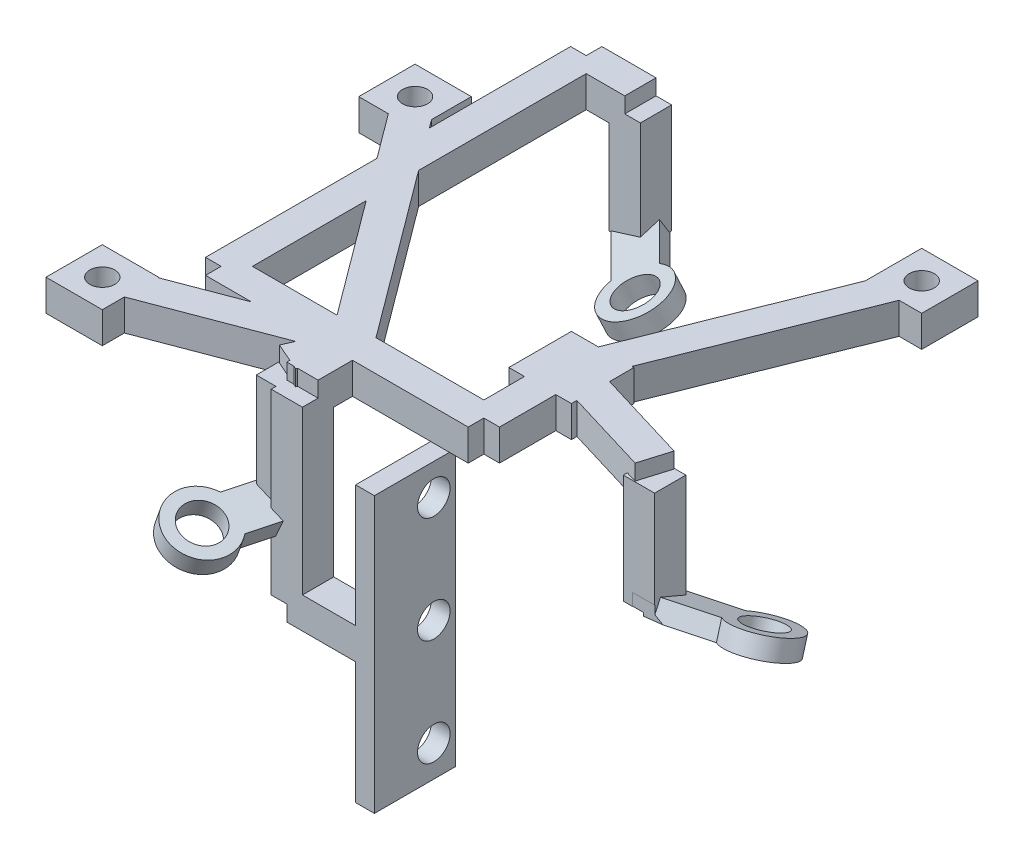
SolidWorks part; units mm, degrees
other "Cable Fairlead Support Frame"
other "Cable Fairlead Support Frame Left"
ref_plane "Front Plane" through (0, 0, 0) normal (0, 0, 1) x (1, 0, 0)
ref_plane "Top Plane" through (0, 0, 0) normal (0, 1, 0) x (1, 0, 0)
ref_plane "Right Plane" through (0, 0, 0) normal (1, 0, 0) x (0, 0, -1)
sketch3d "Cable Fairlead Support Frame Feature profile datum points"
  point P0 (-55.2917, -60, -5)
  point P1 (-45.2917, -60, -5)
  point P2 (-55.2917, -50, -5)
ref_plane "Cable Fairlead Support Frame Feature profile plane" through (0, 0, -5) normal (0, 0, 1) x (1, 0, 0)
sketch "Cable Fairlead Support Frame Feature profile" plane through (0, 0, -5) normal (0, 0, 1) x (1, 0, 0)
  line L0 (-55.2917, -60) -> (-45.2917, -60)
  line L1 (-45.2917, -60) -> (-45.2917, -55)
  line L2 (-45.2917, -55) -> (-55.2917, -55)
  line L3 (-55.2917, -55) -> (-55.2917, -60)
extrude "Cable Fairlead Support Frame Feature" add sketch "Cable Fairlead Support Frame Feature profile" along normal blind 10 separate body
sketch3d "Frame Upper Trunk Sketch datum points"
  point P0 (-50.2917, -57.5, 0)
  point P1 (-40.2917, -57.5, 0)
  point P2 (-50.2917, -47.5, 0)
ref_plane "Frame Upper Trunk Sketch plane" through (0, 0, 0) normal (0, 0, 1) x (1, 0, 0)
sketch "Frame Upper Trunk Sketch" plane through (0, 0, 0) normal (0, 0, 1) x (1, 0, 0)
  line L0 (-52.7917, -60) -> (-47.7917, -60)
  line L1 (-47.7917, -60) -> (-47.7917, -55)
  line L2 (-47.7917, -55) -> (-52.7917, -55)
  line L3 (-52.7917, -55) -> (-52.7917, -60)
extrude "Frame Upper Trunk Feature" add sketch "Frame Upper Trunk Sketch" along normal blind 14
sketch3d "Frame Left Trunk Sketch datum points"
  point P0 (-50.2917, -57.5, 14)
  point P1 (-50.2917, -57.5, 24)
  point P2 (-50.2917, -47.5, 14)
ref_plane "Frame Left Trunk Sketch plane" through (-50.2917, 0, 0) normal (-1, 0, 0) x (0, 0, 1)
sketch "Frame Left Trunk Sketch" plane through (-50.2917, 0, 0) normal (-1, 0, 0) x (0, 0, 1)
  line L0 (11.5, -60) -> (16.5, -60)
  line L1 (16.5, -60) -> (16.5, -55)
  line L2 (16.5, -55) -> (11.5, -55)
  line L3 (11.5, -55) -> (11.5, -60)
extrude "Frame Left Trunk Feature" add sketch "Frame Left Trunk Sketch" along normal blind 21
sketch3d "Fixed Frame Mounting Web 1 Sketch datum points"
  point P0 (-71.2917, -57.5, 14)
  point P1 (-79.3163, -57.5, 19.967)
  point P2 (-71.2917, -47.5, 14)
ref_plane "Fixed Frame Mounting Web 1 Sketch plane" through (-18.6801, 0, -25.1214) normal (-0.5967, 0, -0.8025) x (-0.8025, 0, 0.5967)
sketch "Fixed Frame Mounting Web 1 Sketch" plane through (-18.6801, 0, -25.1214) normal (-0.5967, 0, -0.8025) x (-0.8025, 0, 0.5967)
  line L0 (63.0627, -60) -> (68.0627, -60)
  line L1 (68.0627, -60) -> (68.0627, -55)
  line L2 (68.0627, -55) -> (63.0627, -55)
  line L3 (63.0627, -55) -> (63.0627, -60)
extrude "Fixed Frame Mounting Web 1 Feature" add sketch "Fixed Frame Mounting Web 1 Sketch" along normal blind 48.6004
sketch3d "Prismatic M4 Mounting Pad 1 profile datum points"
  point P0 (-104.7917, -60, -29.5)
  point P1 (-94.7917, -60, -29.5)
  point P2 (-104.7917, -50, -29.5)
ref_plane "Prismatic M4 Mounting Pad 1 profile plane" through (0, 0, -29.5) normal (0, 0, 1) x (1, 0, 0)
sketch "Prismatic M4 Mounting Pad 1 profile" plane through (0, 0, -29.5) normal (0, 0, 1) x (1, 0, 0)
  line L0 (-104.7917, -60) -> (-95.7917, -60)
  line L1 (-95.7917, -60) -> (-95.7917, -55)
  line L2 (-95.7917, -55) -> (-104.7917, -55)
  line L3 (-104.7917, -55) -> (-104.7917, -60)
extrude "Prismatic M4 Mounting Pad 1" add sketch "Prismatic M4 Mounting Pad 1 profile" along normal blind 9
sketch3d "Nominal M4 Mounting Thread 1 profile datum points"
  point P0 (-100.2917, -51, -25)
  point P1 (-90.2917, -51, -25)
  point P2 (-100.2917, -51, -15)
ref_plane "Nominal M4 Mounting Thread 1 profile plane" through (0, -51, 0) normal (0, -1, 0) x (-1, 0, 0)
sketch "Nominal M4 Mounting Thread 1 profile" plane through (0, -51, 0) normal (0, -1, 0) x (-1, 0, 0)
  circle A0 centre (100.2917, 25) radius 2
extrude "Nominal M4 Mounting Thread 1" cut sketch "Nominal M4 Mounting Thread 1 profile" along normal blind 9.1
sketch3d "Fixed Frame Mounting Web 2 Sketch datum points"
  point P0 (-71.2917, -57.5, 14)
  point P1 (-67.7451, -57.5, 23.35)
  point P2 (-71.2917, -47.5, 14)
ref_plane "Fixed Frame Mounting Web 2 Sketch plane" through (-66.967, 0, 25.4013) normal (-0.935, 0, 0.3547) x (0.3547, 0, 0.935)
sketch "Fixed Frame Mounting Web 2 Sketch" plane through (-66.967, 0, 25.4013) normal (-0.935, 0, 0.3547) x (0.3547, 0, 0.935)
  line L0 (-14.6939, -60) -> (-9.6939, -60)
  line L1 (-9.6939, -60) -> (-9.6939, -55)
  line L2 (-9.6939, -55) -> (-14.6939, -55)
  line L3 (-14.6939, -55) -> (-14.6939, -60)
extrude "Fixed Frame Mounting Web 2 Feature" add sketch "Fixed Frame Mounting Web 2 Sketch" along normal blind 31.0161
sketch3d "Prismatic M4 Mounting Pad 2 profile datum points"
  point P0 (-104.7917, -60, 20.5)
  point P1 (-94.7917, -60, 20.5)
  point P2 (-104.7917, -50, 20.5)
ref_plane "Prismatic M4 Mounting Pad 2 profile plane" through (0, 0, 20.5) normal (0, 0, 1) x (1, 0, 0)
sketch "Prismatic M4 Mounting Pad 2 profile" plane through (0, 0, 20.5) normal (0, 0, 1) x (1, 0, 0)
  line L0 (-104.7917, -60) -> (-95.7917, -60)
  line L1 (-95.7917, -60) -> (-95.7917, -55)
  line L2 (-95.7917, -55) -> (-104.7917, -55)
  line L3 (-104.7917, -55) -> (-104.7917, -60)
extrude "Prismatic M4 Mounting Pad 2" add sketch "Prismatic M4 Mounting Pad 2 profile" along normal blind 9
sketch3d "Nominal M4 Mounting Thread 2 profile datum points"
  point P0 (-100.2917, -51, 25)
  point P1 (-90.2917, -51, 25)
  point P2 (-100.2917, -51, 35)
ref_plane "Nominal M4 Mounting Thread 2 profile plane" through (0, -51, 0) normal (0, -1, 0) x (-1, 0, 0)
sketch "Nominal M4 Mounting Thread 2 profile" plane through (0, -51, 0) normal (0, -1, 0) x (-1, 0, 0)
  circle A0 centre (100.2917, -25) radius 2
extrude "Nominal M4 Mounting Thread 2" cut sketch "Nominal M4 Mounting Thread 2 profile" along normal blind 9.1
sketch3d "Fixed Frame Mounting Web 3 Sketch datum points"
  point P0 (-50.2917, -57.5, 0)
  point P1 (-59.5764, -57.5, -3.7139)
  point P2 (-50.2917, -47.5, 0)
ref_plane "Fixed Frame Mounting Web 3 Sketch plane" through (-6.9368, 0, 17.3419) normal (0.3714, 0, -0.9285) x (-0.9285, 0, -0.3714)
sketch "Fixed Frame Mounting Web 3 Sketch" plane through (-6.9368, 0, 17.3419) normal (0.3714, 0, -0.9285) x (-0.9285, 0, -0.3714)
  line L0 (44.1946, -60) -> (49.1946, -60)
  line L1 (49.1946, -60) -> (49.1946, -55)
  line L2 (49.1946, -55) -> (44.1946, -55)
  line L3 (44.1946, -55) -> (44.1946, -60)
extrude "Fixed Frame Mounting Web 3 Feature" add sketch "Fixed Frame Mounting Web 3 Sketch" along normal blind 43.0813
sketch3d "Prismatic M4 Mounting Pad 3 profile datum points"
  point P0 (-38.7917, -60, -44.5)
  point P1 (-28.7917, -60, -44.5)
  point P2 (-38.7917, -50, -44.5)
ref_plane "Prismatic M4 Mounting Pad 3 profile plane" through (0, 0, -44.5) normal (0, 0, 1) x (1, 0, 0)
sketch "Prismatic M4 Mounting Pad 3 profile" plane through (0, 0, -44.5) normal (0, 0, 1) x (1, 0, 0)
  line L0 (-38.7917, -60) -> (-29.7917, -60)
  line L1 (-29.7917, -60) -> (-29.7917, -55)
  line L2 (-29.7917, -55) -> (-38.7917, -55)
  line L3 (-38.7917, -55) -> (-38.7917, -60)
extrude "Prismatic M4 Mounting Pad 3" add sketch "Prismatic M4 Mounting Pad 3 profile" along normal blind 9
sketch3d "Nominal M4 Mounting Thread 3 profile datum points"
  point P0 (-34.2917, -51, -40)
  point P1 (-24.2917, -51, -40)
  point P2 (-34.2917, -51, -30)
ref_plane "Nominal M4 Mounting Thread 3 profile plane" through (0, -51, 0) normal (0, -1, 0) x (-1, 0, 0)
sketch "Nominal M4 Mounting Thread 3 profile" plane through (0, -51, 0) normal (0, -1, 0) x (-1, 0, 0)
  circle A0 centre (34.2917, 40) radius 2
extrude "Nominal M4 Mounting Thread 3" cut sketch "Nominal M4 Mounting Thread 3 profile" along normal blind 9.1
sketch3d "Outlet Side Rise Sketch datum points"
  point P0 (-71.2917, -57.5, 14)
  point P1 (-61.2917, -57.5, 14)
  point P2 (-71.2917, -47.5, 14)
ref_plane "Outlet Side Rise Sketch plane" through (0, 0, 14) normal (0, 0, 1) x (1, 0, 0)
sketch "Outlet Side Rise Sketch" plane through (0, 0, 14) normal (0, 0, 1) x (1, 0, 0)
  line L0 (-73.7917, -60) -> (-68.7917, -60)
  line L1 (-68.7917, -60) -> (-68.7917, -55)
  line L2 (-68.7917, -55) -> (-73.7917, -55)
  line L3 (-73.7917, -55) -> (-73.7917, -60)
extrude "Outlet Side Rise Feature" add sketch "Outlet Side Rise Sketch" along normal blind 8
sketch3d "Outlet Lateral Return Sketch datum points"
  point P0 (-71.2917, -57.5, 22)
  point P1 (-61.2917, -57.5, 22)
  point P2 (-71.2917, -57.5, 12)
ref_plane "Outlet Lateral Return Sketch plane" through (0, -57.5, 0) normal (0, 1, 0) x (1, 0, 0)
sketch "Outlet Lateral Return Sketch" plane through (0, -57.5, 0) normal (0, 1, 0) x (1, 0, 0)
  line L0 (-73.7917, -24.5) -> (-68.7917, -24.5)
  line L1 (-68.7917, -24.5) -> (-68.7917, -19.5)
  line L2 (-68.7917, -19.5) -> (-73.7917, -19.5)
  line L3 (-73.7917, -19.5) -> (-73.7917, -24.5)
extrude "Outlet Lateral Return Feature" add sketch "Outlet Lateral Return Sketch" along normal blind 28.5
sketch3d "Outlet Rail Bridge Sketch datum points"
  point P0 (-71.2917, -29, 22)
  point P1 (-71.2917, -29, 12)
  point P2 (-71.2917, -19, 22)
ref_plane "Outlet Rail Bridge Sketch plane" through (-71.2917, 0, 0) normal (1, 0, 0) x (0, 0, -1)
sketch "Outlet Rail Bridge Sketch" plane through (-71.2917, 0, 0) normal (1, 0, 0) x (0, 0, -1)
  line L0 (-24.5, -31.5) -> (-19.5, -31.5)
  line L1 (-19.5, -31.5) -> (-19.5, -26.5)
  line L2 (-19.5, -26.5) -> (-24.5, -26.5)
  line L3 (-24.5, -26.5) -> (-24.5, -31.5)
extrude "Outlet Rail Bridge Feature" add sketch "Outlet Rail Bridge Sketch" along normal blind 13
sketch3d "Integral Three Lane Cable Outlet Clamp Rail profile datum points"
  point P0 (-60.2917, -51, 11.5)
  point P1 (-50.2917, -51, 11.5)
  point P2 (-60.2917, -41, 11.5)
ref_plane "Integral Three Lane Cable Outlet Clamp Rail profile plane" through (0, 0, 11.5) normal (0, 0, 1) x (1, 0, 0)
sketch "Integral Three Lane Cable Outlet Clamp Rail profile" plane through (0, 0, 11.5) normal (0, 0, 1) x (1, 0, 0)
  line L0 (-60.2917, -51) -> (-57.2917, -51)
  line L1 (-57.2917, -51) -> (-57.2917, -7)
  line L2 (-57.2917, -7) -> (-60.2917, -7)
  line L3 (-60.2917, -7) -> (-60.2917, -51)
extrude "Integral Three Lane Cable Outlet Clamp Rail" add sketch "Integral Three Lane Cable Outlet Clamp Rail profile" along normal blind 13
sketch3d "Inlet Outrigger Web 1 Sketch datum points"
  point P0 (-50.2917, -57.5, 0)
  point P1 (-47.4006, -57.5, -9.573)
  point P2 (-50.2917, -47.5, 0)
ref_plane "Inlet Outrigger Web 1 Sketch plane" through (-46.0882, 0, -13.9187) normal (0.9573, 0, 0.2891) x (0.2891, 0, -0.9573)
sketch "Inlet Outrigger Web 1 Sketch" plane through (-46.0882, 0, -13.9187) normal (0.9573, 0, 0.2891) x (0.2891, 0, -0.9573)
  line L0 (-17.0396, -60) -> (-12.0396, -60)
  line L1 (-12.0396, -60) -> (-12.0396, -55)
  line L2 (-12.0396, -55) -> (-17.0396, -55)
  line L3 (-17.0396, -55) -> (-17.0396, -60)
extrude "Inlet Outrigger Web 1 Feature" add sketch "Inlet Outrigger Web 1 Sketch" along normal blind 19.8971
sketch3d "Inlet Vertical Support 1 Sketch datum points"
  point P0 (-31.2442, -57.5, 5.7524)
  point P1 (-21.2442, -57.5, 5.7524)
  point P2 (-31.2442, -57.5, -4.2476)
ref_plane "Inlet Vertical Support 1 Sketch plane" through (0, -57.5, 0) normal (0, 1, 0) x (1, 0, 0)
sketch "Inlet Vertical Support 1 Sketch" plane through (0, -57.5, 0) normal (0, 1, 0) x (1, 0, 0)
  line L0 (-33.7442, -8.2524) -> (-28.7442, -8.2524)
  line L1 (-28.7442, -8.2524) -> (-28.7442, -3.2524)
  line L2 (-28.7442, -3.2524) -> (-33.7442, -3.2524)
  line L3 (-33.7442, -3.2524) -> (-33.7442, -8.2524)
extrude "Inlet Vertical Support 1 Feature" add sketch "Inlet Vertical Support 1 Sketch" along normal blind 17.4581
sketch3d "Inlet Collar Retaining Web 1 Sketch datum points"
  point P0 (-31.2442, -40.0419, 5.7524)
  point P1 (-32.2823, -49.2023, 1.8781)
  point P2 (-33.6151, -36.031, -3.0959)
ref_plane "Inlet Collar Retaining Web 1 Sketch plane" through (-30.5893, 0, 8.1964) normal (0.9659, 0, -0.2588) x (-0.2588, 0, -0.9659)
sketch "Inlet Collar Retaining Web 1 Sketch" plane through (-30.5893, 0, 8.1964) normal (0.9659, 0, -0.2588) x (-0.2588, 0, -0.9659)
  line L0 (-0.8175, -39.8757) -> (0.3818, -42.6147)
  line L1 (0.3818, -42.6147) -> (5.878, -40.2081)
  line L2 (5.878, -40.2081) -> (4.6787, -37.4692)
  line L3 (4.6787, -37.4692) -> (-0.8175, -39.8757)
extrude "Inlet Collar Retaining Web 1 Feature" add sketch "Inlet Collar Retaining Web 1 Sketch" along normal blind 14
sketch3d "Integral Cable Guide Clamp 1 profile datum points"
  point P0 (-17.566, -38.6724, 2.7081)
  point P1 (-7.6201, -39.6285, 2.3037)
  point P2 (-17.566, -42.5677, 11.9182)
ref_plane "Integral Cable Guide Clamp 1 profile plane" through (-3.7579, -33.1604, -14.0246) normal (-0.1038, -0.916, -0.3874) x (-0.9946, 0.0956, 0.0404)
sketch "Integral Cable Guide Clamp 1 profile" plane through (-3.7579, -33.1604, -14.0246) normal (-0.1038, -0.916, -0.3874) x (-0.9946, 0.0956, 0.0404)
  circle A0 centre (13.8831, -17.5581) radius 5
extrude "Integral Cable Guide Clamp 1" add sketch "Integral Cable Guide Clamp 1 profile" along normal blind 2.99
sketch3d "Final Cable Inlet Clamp Through Bore 1 profile datum points"
  point P0 (-17.5546, -38.5717, 2.7507)
  point P1 (-7.6086, -39.5278, 2.3463)
  point P2 (-17.5546, -42.4669, 11.9609)
ref_plane "Final Cable Inlet Clamp Through Bore 1 profile plane" through (-3.7465, -33.0597, -13.982) normal (-0.1038, -0.916, -0.3874) x (-0.9946, 0.0956, 0.0404)
sketch "Final Cable Inlet Clamp Through Bore 1 profile" plane through (-3.7465, -33.0597, -13.982) normal (-0.1038, -0.916, -0.3874) x (-0.9946, 0.0956, 0.0404)
  circle A0 centre (13.8831, -17.5581) radius 3.1
extrude "Final Cable Inlet Clamp Through Bore 1" cut sketch "Final Cable Inlet Clamp Through Bore 1 profile" along normal blind 7.2
sketch3d "Inlet Outrigger Web 2 Sketch datum points"
  point P0 (-71.2917, -57.5, 14)
  point P1 (-62.124, -57.5, 17.9944)
  point P2 (-71.2917, -47.5, 14)
ref_plane "Inlet Outrigger Web 2 Sketch plane" through (-16.5011, 0, 37.8724) normal (-0.3994, 0, 0.9168) x (0.9168, 0, 0.3994)
sketch "Inlet Outrigger Web 2 Sketch" plane through (-16.5011, 0, 37.8724) normal (-0.3994, 0, 0.9168) x (0.9168, 0, 0.3994)
  line L0 (-62.2653, -60) -> (-57.2653, -60)
  line L1 (-57.2653, -60) -> (-57.2653, -55)
  line L2 (-57.2653, -55) -> (-62.2653, -55)
  line L3 (-62.2653, -55) -> (-62.2653, -60)
extrude "Inlet Outrigger Web 2 Feature" add sketch "Inlet Outrigger Web 2 Sketch" along normal blind 7.8874
sketch3d "Inlet Vertical Support 2 Sketch datum points"
  point P0 (-74.4422, -57.5, 21.2309)
  point P1 (-64.4422, -57.5, 21.2309)
  point P2 (-74.4422, -57.5, 11.2309)
ref_plane "Inlet Vertical Support 2 Sketch plane" through (0, -57.5, 0) normal (0, 1, 0) x (1, 0, 0)
sketch "Inlet Vertical Support 2 Sketch" plane through (0, -57.5, 0) normal (0, 1, 0) x (1, 0, 0)
  line L0 (-76.9422, -23.7309) -> (-71.9422, -23.7309)
  line L1 (-71.9422, -23.7309) -> (-71.9422, -18.7309)
  line L2 (-71.9422, -18.7309) -> (-76.9422, -18.7309)
  line L3 (-76.9422, -18.7309) -> (-76.9422, -23.7309)
extrude "Inlet Vertical Support 2 Feature" add sketch "Inlet Vertical Support 2 Sketch" along normal blind 17.4535
sketch3d "Inlet Collar Retaining Web 2 Sketch datum points"
  point P0 (-74.4422, -40.0465, 21.2309)
  point P1 (-70.568, -49.2069, 22.269)
  point P2 (-65.5939, -36.0356, 23.6018)
ref_plane "Inlet Collar Retaining Web 2 Sketch plane" through (-10.2944, 0, 38.4192) normal (-0.2588, 0, 0.9659) x (0.9659, 0, 0.2588)
sketch "Inlet Collar Retaining Web 2 Sketch" plane through (-10.2944, 0, 38.4192) normal (-0.2588, 0, 0.9659) x (0.9659, 0, 0.2588)
  line L0 (-69.7564, -39.8849) -> (-68.5612, -42.6147)
  line L1 (-68.5612, -42.6147) -> (-63.0649, -40.2081)
  line L2 (-63.0649, -40.2081) -> (-64.2602, -37.4783)
  line L3 (-64.2602, -37.4783) -> (-69.7564, -39.8849)
extrude "Inlet Collar Retaining Web 2 Feature" add sketch "Inlet Collar Retaining Web 2 Sketch" along normal blind 11.5
sketch3d "Integral Cable Guide Clamp 2 profile datum points"
  point P0 (-77.9959, -38.6816, 32.1844)
  point P1 (-68.7768, -34.832, 31.7481)
  point P2 (-77.9959, -37.5556, 42.1208)
ref_plane "Integral Cable Guide Clamp 2 profile plane" through (3.3154, -7.839, 0.8884) normal (0.3874, -0.916, 0.1038) x (-0.9219, -0.385, 0.0436)
sketch "Integral Cable Guide Clamp 2 profile" plane through (3.3154, -7.839, 0.8884) normal (0.3874, -0.916, 0.1038) x (-0.9219, -0.385, 0.0436)
  circle A0 centre (88.1994, -27.624) radius 5
extrude "Integral Cable Guide Clamp 2" add sketch "Integral Cable Guide Clamp 2 profile" along normal blind 2.98
sketch3d "Final Cable Inlet Clamp Through Bore 2 profile datum points"
  point P0 (-78.0424, -38.5717, 32.1719)
  point P1 (-68.8233, -34.7221, 31.7357)
  point P2 (-78.0424, -37.4456, 42.1083)
ref_plane "Final Cable Inlet Clamp Through Bore 2 profile plane" through (3.2689, -7.7291, 0.8759) normal (0.3874, -0.916, 0.1038) x (-0.9219, -0.385, 0.0436)
sketch "Final Cable Inlet Clamp Through Bore 2 profile" plane through (3.2689, -7.7291, 0.8759) normal (0.3874, -0.916, 0.1038) x (-0.9219, -0.385, 0.0436)
  circle A0 centre (88.1994, -27.624) radius 3.1
extrude "Final Cable Inlet Clamp Through Bore 2" cut sketch "Final Cable Inlet Clamp Through Bore 2 profile" along normal blind 7.2
sketch3d "Third Inlet Cable Sweep Left Bypass Sketch datum points"
  point P0 (-71.2917, -57.5, 14)
  point P1 (-71.2917, -57.5, 24)
  point P2 (-71.2917, -47.5, 14)
ref_plane "Third Inlet Cable Sweep Left Bypass Sketch plane" through (-71.2917, 0, 0) normal (-1, 0, 0) x (0, 0, 1)
sketch "Third Inlet Cable Sweep Left Bypass Sketch" plane through (-71.2917, 0, 0) normal (-1, 0, 0) x (0, 0, 1)
  line L0 (11.5, -60) -> (16.5, -60)
  line L1 (16.5, -60) -> (16.5, -55)
  line L2 (16.5, -55) -> (11.5, -55)
  line L3 (11.5, -55) -> (11.5, -60)
extrude "Third Inlet Cable Sweep Left Bypass Feature" add sketch "Third Inlet Cable Sweep Left Bypass Sketch" along normal blind 21
sketch3d "Third Inlet Cable Sweep Lower Bypass Sketch datum points"
  point P0 (-92.2917, -57.5, 14)
  point P1 (-102.2917, -57.5, 14)
  point P2 (-92.2917, -47.5, 14)
ref_plane "Third Inlet Cable Sweep Lower Bypass Sketch plane" through (0, 0, 14) normal (0, 0, -1) x (-1, 0, 0)
sketch "Third Inlet Cable Sweep Lower Bypass Sketch" plane through (0, 0, 14) normal (0, 0, -1) x (-1, 0, 0)
  line L0 (89.7917, -60) -> (94.7917, -60)
  line L1 (94.7917, -60) -> (94.7917, -55)
  line L2 (94.7917, -55) -> (89.7917, -55)
  line L3 (89.7917, -55) -> (89.7917, -60)
extrude "Third Inlet Cable Sweep Lower Bypass Feature" add sketch "Third Inlet Cable Sweep Lower Bypass Sketch" along normal blind 58.3669
sketch3d "Third Inlet Cable Sweep Return Sketch datum points"
  point P0 (-92.2917, -57.5, -44.3669)
  point P1 (-92.2917, -57.5, -54.3669)
  point P2 (-92.2917, -47.5, -44.3669)
ref_plane "Third Inlet Cable Sweep Return Sketch plane" through (-92.2917, 0, 0) normal (1, 0, 0) x (0, 0, -1)
sketch "Third Inlet Cable Sweep Return Sketch" plane through (-92.2917, 0, 0) normal (1, 0, 0) x (0, 0, -1)
  line L0 (41.8669, -60) -> (46.8669, -60)
  line L1 (46.8669, -60) -> (46.8669, -55)
  line L2 (46.8669, -55) -> (41.8669, -55)
  line L3 (41.8669, -55) -> (41.8669, -60)
extrude "Third Inlet Cable Sweep Return Feature" add sketch "Third Inlet Cable Sweep Return Sketch" along normal blind 8.659
sketch3d "Inlet Vertical Support 3 Sketch datum points"
  point P0 (-83.6327, -57.5, -44.3669)
  point P1 (-73.6327, -57.5, -44.3669)
  point P2 (-83.6327, -57.5, -54.3669)
ref_plane "Inlet Vertical Support 3 Sketch plane" through (0, -57.5, 0) normal (0, 1, 0) x (1, 0, 0)
sketch "Inlet Vertical Support 3 Sketch" plane through (0, -57.5, 0) normal (0, 1, 0) x (1, 0, 0)
  line L0 (-86.1327, 41.8669) -> (-81.1327, 41.8669)
  line L1 (-81.1327, 41.8669) -> (-81.1327, 46.8669)
  line L2 (-81.1327, 46.8669) -> (-86.1327, 46.8669)
  line L3 (-86.1327, 46.8669) -> (-86.1327, 41.8669)
extrude "Inlet Vertical Support 3 Feature" add sketch "Inlet Vertical Support 3 Sketch" along normal blind 17.4581
sketch3d "Inlet Collar Retaining Web 3 Sketch datum points"
  point P0 (-83.6327, -40.0419, -44.3669)
  point P1 (-86.4688, -49.2023, -41.5308)
  point P2 (-77.1553, -44.0528, -50.8443)
ref_plane "Inlet Collar Retaining Web 3 Sketch plane" through (-63.9998, 0, -63.9998) normal (0.7071, 0, 0.7071) x (0.7071, 0, -0.7071)
sketch "Inlet Collar Retaining Web 3 Sketch" plane through (-63.9998, 0, -63.9998) normal (0.7071, 0, 0.7071) x (0.7071, 0, -0.7071)
  line L0 (-29.9136, -37.4692) -> (-31.1128, -40.2081)
  line L1 (-31.1128, -40.2081) -> (-25.6166, -42.6147)
  line L2 (-25.6166, -42.6147) -> (-24.4174, -39.8757)
  line L3 (-24.4174, -39.8757) -> (-29.9136, -37.4692)
extrude "Inlet Collar Retaining Web 3 Feature" add sketch "Inlet Collar Retaining Web 3 Sketch" along normal blind 14
sketch3d "Integral Cable Guide Clamp 3 profile datum points"
  point P0 (-73.3092, -38.6724, -34.8914)
  point P1 (-63.7198, -41.3817, -34.0526)
  point P2 (-73.3092, -35.7149, -25.3388)
ref_plane "Integral Cable Guide Clamp 3 profile plane" through (-13.1373, -42.4321, 13.1373) normal (-0.2836, -0.916, 0.2836) x (-0.9589, 0.2709, -0.0839)
sketch "Integral Cable Guide Clamp 3 profile" plane through (-13.1373, -42.4321, 13.1373) normal (-0.2836, -0.916, 0.2836) x (-0.9589, 0.2709, -0.0839)
  circle A0 centre (62.7484, 44.7681) radius 5
extrude "Integral Cable Guide Clamp 3" add sketch "Integral Cable Guide Clamp 3 profile" along normal blind 2.99
sketch3d "Final Cable Inlet Clamp Through Bore 3 profile datum points"
  point P0 (-73.278, -38.5717, -34.9226)
  point P1 (-63.6886, -41.2809, -34.0838)
  point P2 (-73.278, -35.6141, -25.37)
ref_plane "Final Cable Inlet Clamp Through Bore 3 profile plane" through (-13.1061, -42.3313, 13.1061) normal (-0.2836, -0.916, 0.2836) x (-0.9589, 0.2709, -0.0839)
sketch "Final Cable Inlet Clamp Through Bore 3 profile" plane through (-13.1061, -42.3313, 13.1061) normal (-0.2836, -0.916, 0.2836) x (-0.9589, 0.2709, -0.0839)
  circle A0 centre (62.7484, 44.7681) radius 3.1
extrude "Final Cable Inlet Clamp Through Bore 3" cut sketch "Final Cable Inlet Clamp Through Bore 3 profile" along normal blind 7.2
sketch3d "Cable Outlet Clamp Bore 1 profile datum points"
  point P0 (-62.3917, -12, 15)
  point P1 (-62.3917, -2, 15)
  point P2 (-62.3917, -12, 25)
ref_plane "Cable Outlet Clamp Bore 1 profile plane" through (-62.3917, 0, 0) normal (1, 0, 0) x (0, 0, -1)
sketch "Cable Outlet Clamp Bore 1 profile" plane through (-62.3917, 0, 0) normal (1, 0, 0) x (0, 0, -1)
  circle A0 centre (-15, -12) radius 2.6
extrude "Cable Outlet Clamp Bore 1" cut sketch "Cable Outlet Clamp Bore 1 profile" along normal blind 7.4
sketch3d "Cable Outlet Clamp Bore 2 profile datum points"
  point P0 (-62.3917, -29, 15)
  point P1 (-62.3917, -19, 15)
  point P2 (-62.3917, -29, 25)
ref_plane "Cable Outlet Clamp Bore 2 profile plane" through (-62.3917, 0, 0) normal (1, 0, 0) x (0, 0, -1)
sketch "Cable Outlet Clamp Bore 2 profile" plane through (-62.3917, 0, 0) normal (1, 0, 0) x (0, 0, -1)
  circle A0 centre (-15, -29) radius 2.6
extrude "Cable Outlet Clamp Bore 2" cut sketch "Cable Outlet Clamp Bore 2 profile" along normal blind 7.4
sketch3d "Outlet Rear Nut Seating Clearance 2 profile datum points"
  point P0 (-62.3917, -29, 15)
  point P1 (-62.3917, -19, 15)
  point P2 (-62.3917, -29, 25)
ref_plane "Outlet Rear Nut Seating Clearance 2 profile plane" through (-62.3917, 0, 0) normal (1, 0, 0) x (0, 0, -1)
sketch "Outlet Rear Nut Seating Clearance 2 profile" plane through (-62.3917, 0, 0) normal (1, 0, 0) x (0, 0, -1)
  circle A0 centre (-15, -29) radius 4.75
extrude "Outlet Rear Nut Seating Clearance 2" cut sketch "Outlet Rear Nut Seating Clearance 2 profile" along normal blind 2.1
sketch3d "Cable Outlet Clamp Bore 3 profile datum points"
  point P0 (-62.3917, -46, 15)
  point P1 (-62.3917, -36, 15)
  point P2 (-62.3917, -46, 25)
ref_plane "Cable Outlet Clamp Bore 3 profile plane" through (-62.3917, 0, 0) normal (1, 0, 0) x (0, 0, -1)
sketch "Cable Outlet Clamp Bore 3 profile" plane through (-62.3917, 0, 0) normal (1, 0, 0) x (0, 0, -1)
  circle A0 centre (-15, -46) radius 2.6
extrude "Cable Outlet Clamp Bore 3" cut sketch "Cable Outlet Clamp Bore 3 profile" along normal blind 7.4
sketch3d "First Inlet Web Comb Corner Clearance profile datum points"
  point P0 (-32.2917, -42, 8.2)
  point P1 (-22.2917, -42, 8.2)
  point P2 (-32.2917, -32, 8.2)
ref_plane "First Inlet Web Comb Corner Clearance profile plane" through (0, 0, 8.2) normal (0, 0, 1) x (1, 0, 0)
sketch "First Inlet Web Comb Corner Clearance profile" plane through (0, 0, 8.2) normal (0, 0, 1) x (1, 0, 0)
  line L0 (-32.2917, -42) -> (-27.2917, -42)
  line L1 (-27.2917, -42) -> (-27.2917, -38)
  line L2 (-27.2917, -38) -> (-32.2917, -38)
  line L3 (-32.2917, -38) -> (-32.2917, -42)
extrude "First Inlet Web Comb Corner Clearance" cut sketch "First Inlet Web Comb Corner Clearance profile" along normal blind 1.3
sketch3d "First Wall Mount Outer Corner Rail Head Clearance profile datum points"
  point P0 (-104.8917, -56.2, -29.6)
  point P1 (-94.8917, -56.2, -29.6)
  point P2 (-104.8917, -46.2, -29.6)
ref_plane "First Wall Mount Outer Corner Rail Head Clearance profile plane" through (0, 0, -29.6) normal (0, 0, 1) x (1, 0, 0)
sketch "First Wall Mount Outer Corner Rail Head Clearance profile" plane through (0, 0, -29.6) normal (0, 0, 1) x (1, 0, 0)
  line L0 (-104.8917, -56.2) -> (-103.0917, -56.2)
  line L1 (-103.0917, -56.2) -> (-103.0917, -54.9)
  line L2 (-103.0917, -54.9) -> (-104.8917, -54.9)
  line L3 (-104.8917, -54.9) -> (-104.8917, -56.2)
extrude "First Wall Mount Outer Corner Rail Head Clearance" cut sketch "First Wall Mount Outer Corner Rail Head Clearance profile" along normal blind 5.1
sketch3d "Mirror1 profile datum points"
  point P0 (0, 0, 0)
  point P1 (10, 0, 0)
  point P2 (0, 0, 10)
ref_plane "Mirror1 profile plane" through (0, 0, 0) normal (0, -1, 0) x (-1, 0, 0)
mirror "Mirror1" about plane through (0, 0, 0) normal (0, -1, 0) of bodies 139
delete or keep bodies "Remove1" type delete bodies bodies 139
